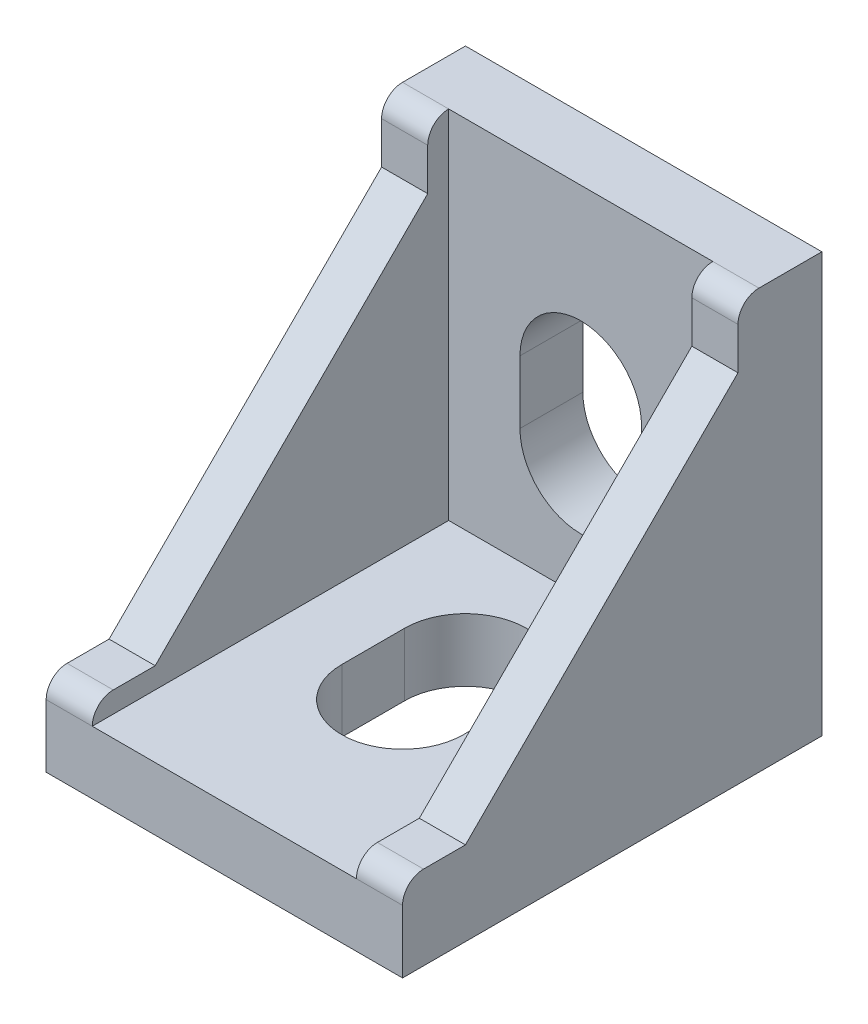
SolidWorks part; units mm, degrees
ref_plane "前视基准面" through (0, 0, 0) normal (0, 0, 1) x (1, 0, 0)
ref_plane "上视基准面" through (0, 0, 0) normal (0, 1, 0) x (1, 0, 0)
ref_plane "右视基准面" through (0, 0, 0) normal (1, 0, 0) x (0, 0, -1)
sketch "草图1" plane through (0, 0, 0) normal (0, 1, 0) x (1, 0, 0)
  line L1 (-8.5, -10) -> (8.5, -10)
  line L2 (-8.5, -10) -> (-8.5, 10)
  line L3 (-8.5, 10) -> (8.5, 10)
  line L4 (8.5, -10) -> (8.5, 10)
  line L5 (-8.5, -10) -> (8.5, 10) construction
  line L6 (-8.5, 10) -> (8.5, -10) construction
  point P0 (0, 0)
  dimension "D1" = 17
  dimension "D2" = 20
extrude "凸台-拉伸1" add sketch "草图1" along normal blind 20
sketch "草图2" plane through (0, 20, 0) normal (0, 1, 0) x (1, 0, 0)
  line L5 (6.3, 7) -> (-6.3, 7)
  line L6 (-6.3, 7) -> (-6.3, -10)
  line L7 (-8.5, -10) -> (8.5, -10) construction
  line L8 (-6.3, -10) -> (6.3, -10)
  line L9 (6.3, -10) -> (6.3, 7)
extrude "切除-拉伸1" cut sketch "草图2" against normal blind 17
sketch "草图3" plane through (8.5, 0, 0) normal (1, 0, 0) x (0, 0, -1)
  line L2 (-10, 20) -> (10, 20) construction
  line L3 (6, 19) -> (6, 17)
  line L5 (-10, 20) -> (-10, 0) construction
  line L6 (-9, 4) -> (-7, 4)
  line L7 (-7, 4) -> (6, 17)
  line L8 (7, 20) -> (-10, 20)
  line L9 (-10, 20) -> (-10, 3)
  arc A0 (7, 20) -> (6, 19) centre (7, 19) ccw
  arc A1 (-10, 3) -> (-9, 4) centre (-9, 3) cw
  point P19 (6, 20)
  point P24 (-10, 4)
  dimension "D1" = 1
extrude "切除-拉伸2" cut sketch "草图3" against normal blind 17
sketch "草图4" plane through (0, 0, -7) normal (0, 0, 1) x (1, 0, 0)
  line L2 (2.9, 11.5) -> (2.9, 8.5)
  line L3 (-2.9, 8.5) -> (-2.9, 11.5)
  arc A0 (2.9, 11.5) -> (-2.9, 11.5) centre (0, 11.5) ccw
  arc A1 (-2.9, 8.5) -> (2.9, 8.5) centre (0, 8.5) ccw
extrude "切除-拉伸3" cut sketch "草图4" against normal blind 3
sketch "草图5" plane through (0, 3, 0) normal (0, 1, 0) x (1, 0, 0)
  line L0 (2.9, 1.5) -> (2.9, -1.5)
  line L1 (-2.9, -1.5) -> (-2.9, 1.5)
  arc A0 (2.9, 1.5) -> (-2.9, 1.5) centre (0, 1.5) ccw
  arc A1 (-2.9, -1.5) -> (2.9, -1.5) centre (0, -1.5) ccw
extrude "切除-拉伸4" cut sketch "草图5" against normal blind 3
